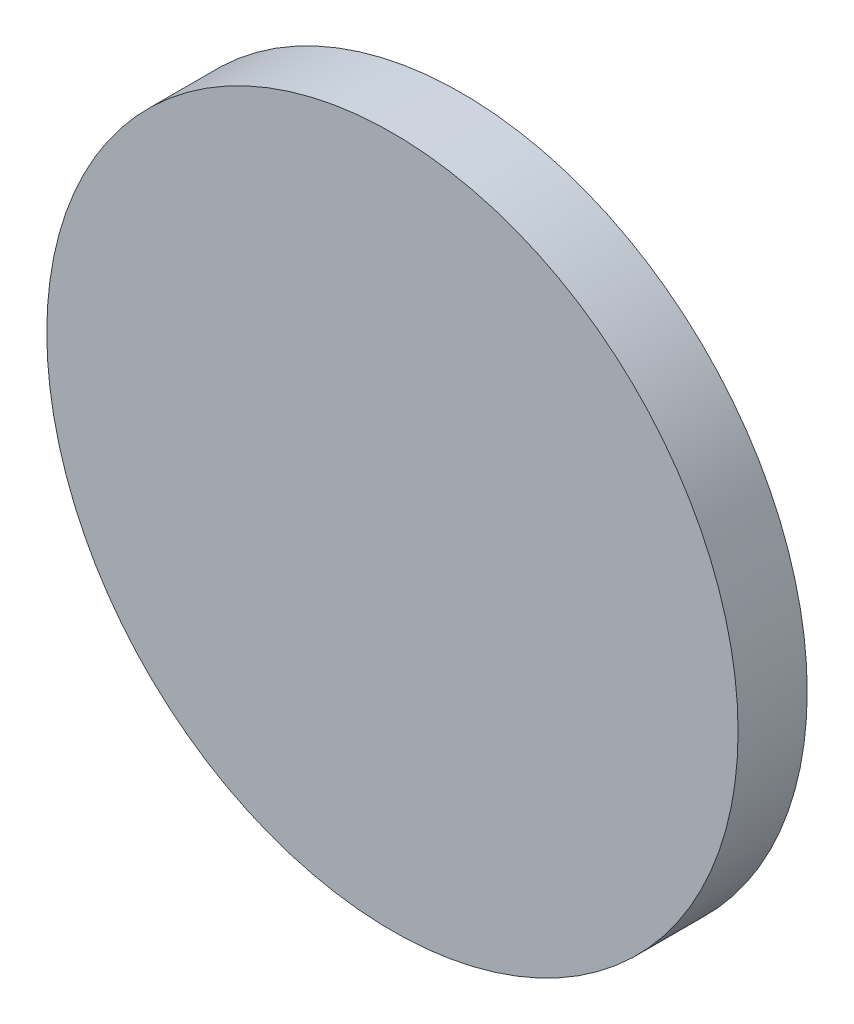
SolidWorks part; units mm, degrees
ref_plane "Plane1" through (0, 0, 0) normal (0, 0, 1) x (1, 0, 0)
ref_plane "Plane2" through (0, 0, 0) normal (0, 1, 0) x (1, 0, 0)
ref_plane "Plane3" through (0, 0, 0) normal (1, 0, 0) x (0, 0, -1)
other "Configuration Table"
sketch "s1" plane through (0, 0, 0) normal (0, 0, 1) x (1, 0, 0)
  circle A1 centre (0, 0) radius 10
extrude "1" add sketch "s1" along normal mid plane 2
